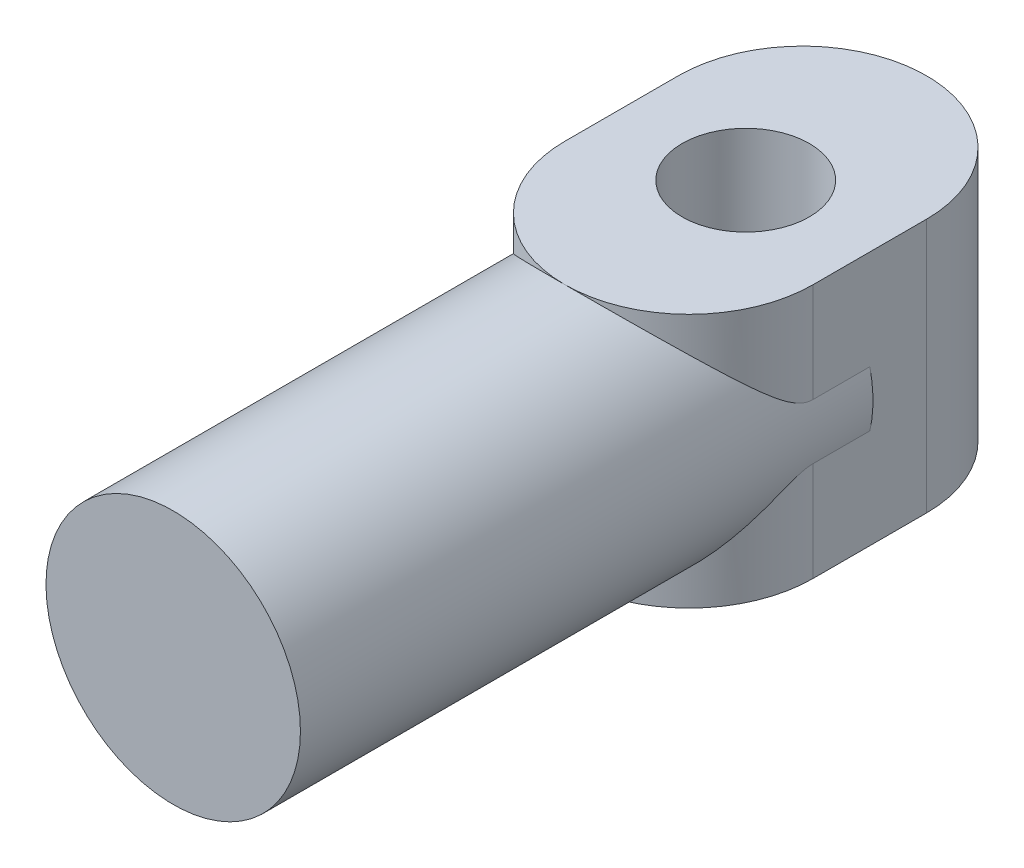
SolidWorks part; units mm, degrees
ref_plane "Front Plane" through (0, 0, 0) normal (0, 0, 1) x (1, 0, 0)
ref_plane "Top Plane" through (0, 0, 0) normal (0, 1, 0) x (1, 0, 0)
ref_plane "Right Plane" through (0, 0, 0) normal (1, 0, 0) x (0, 0, -1)
sketch "Sketch2" plane through (0, 0, 0) normal (0, 0, 1) x (1, 0, 0)
  circle A0 centre (0, 0) radius 5
  dimension "D1" = 10
extrude "Boss-Extrude2" add sketch "Sketch2" along normal blind 22.5
sketch "Sketch3" plane through (0, 0, 0) normal (0, 1, 0) x (1, 0, 0)
  line L0 (0, -2.2298) -> (0, 2.2298) construction
  line L1 (-4.8794, -2.2298) -> (-4.8794, 2.2298)
  line L2 (4.8794, -2.2298) -> (4.8794, 2.2298)
  arc A0 (-4.8794, -2.2298) -> (4.8794, -2.2298) centre (0, -2.2298) ccw
  arc A1 (4.8794, 2.2298) -> (-4.8794, 2.2298) centre (0, 2.2298) ccw
  point P2 (0, 0)
extrude "Boss-Extrude3" add sketch "Sketch3" along normal mid plane 10
sketch "Sketch4" plane through (0, -5, 0) normal (0, -1, 0) x (1, 0, 0)
  circle A0 centre (0, 0) radius 2.5
  dimension "D1" = 5
extrude "Cut-Extrude1" cut sketch "Sketch4" against normal blind 15
